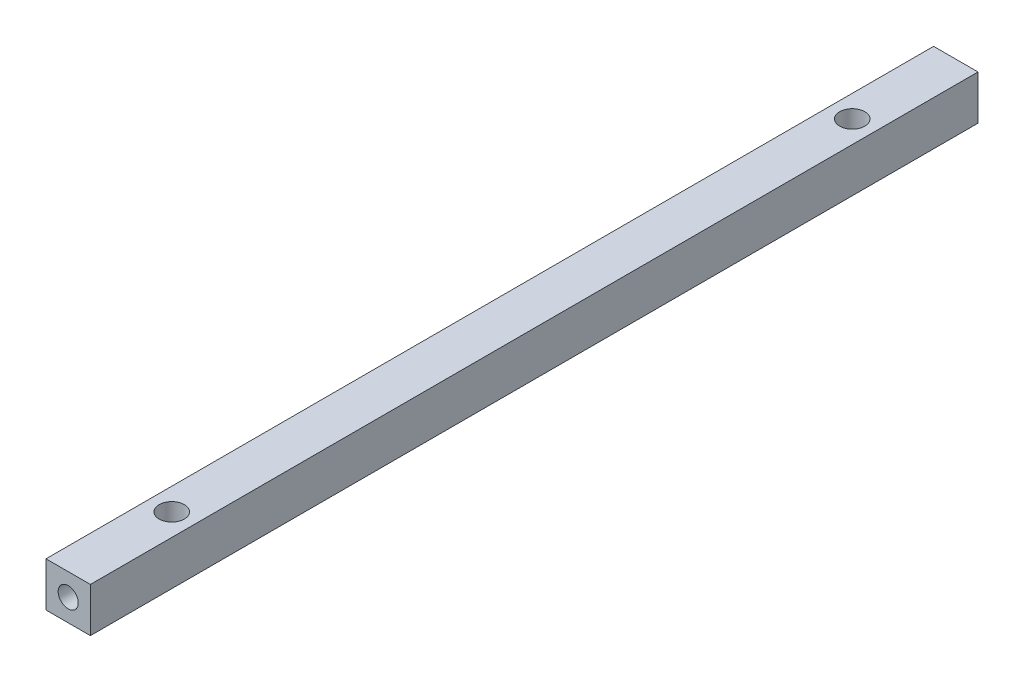
SolidWorks part; units mm, degrees
ref_plane "Ön Düzlem" through (0, 0, 0) normal (0, 0, 1) x (1, 0, 0)
ref_plane "Üst Düzlem" through (0, 0, 0) normal (0, 1, 0) x (1, 0, 0)
ref_plane "Sağ Düzlem" through (0, 0, 0) normal (1, 0, 0) x (0, 0, -1)
sketch "Çizim1" plane through (0, 0, 0) normal (0, 0, 1) x (1, 0, 0)
  line L1 (-7.5, -7.5) -> (7.5, -7.5)
  line L2 (-7.5, -7.5) -> (-7.5, 7.5)
  line L3 (-7.5, 7.5) -> (7.5, 7.5)
  line L4 (7.5, -7.5) -> (7.5, 7.5)
  line L5 (-7.5, -7.5) -> (7.5, 7.5) construction
  line L6 (-7.5, 7.5) -> (7.5, -7.5) construction
  point P0 (0, 0)
  dimension "D1" = 15
extrude "Yükseklik-Ekstrüzyon1" add sketch "Çizim1" along normal mid plane 300
hole_wizard "M8 Dişli Delik1" positions "Çizim2" profile "Çizim3" tap size "M8" standard "ISO"
sketch "Çizim2" plane through (0, 0, 150) normal (0, 0, 1) x (1, 0, 0)
  point P0 (0, 0)
sketch "Çizim3" plane through (0, 0, 150) normal (1, 0, 0) x (0, -1, 0)
  line L0 (0, 0) -> (0, 24.2929)
  line L1 (0, 24.2929) -> (3.4, 22.25)
  line L2 (3.4, 22.25) -> (3.4, 0)
  line L5 (3.4, 0) -> (0, 0)
  line L10 (0, 24.2929) -> (-3.4, 22.25) construction
  line L11 (0, -6.35) -> (0, 107.95) construction
  dimension "Tap Drill Dia." = 6.8
  dimension "Tap Drill Depth" = 22.25
  dimension "Drill Angle" = 118
cosmetic thread "Delik Dişi1" parameters "D1"=16, "D2"=8
mirror "Aynalama1" about plane through (0, 0, 0) normal (0, 0, 1) of "M8 Dişli Delik1"
cosmetic thread "Delik Dişi2" parameters "D1"=16, "D2"=8
hole_wizard "Delik1" positions "Çizim4" profile "Çizim5" legacy
sketch "Çizim4" plane through (0, -7.5, 0) normal (0, -1, 0) x (-1, 0, 0)
  line L0 (7.5, -150) -> (-7.5, -150) construction
  point P0 (0, -115)
  dimension "D1" = 35
sketch "Çizim5" plane through (0, -7.5, 115) normal (1, 0, 0) x (0, 0, -1)
  line L0 (0, 0) -> (0, 15)
  line L1 (0, 15) -> (4.25, 15)
  line L2 (4.25, 15) -> (4.25, 8)
  line L3 (4.25, 8) -> (7, 8)
  line L4 (7, 8) -> (7, 0)
  line L5 (7, 0) -> (0, 0)
  line L6 (0, 110) -> (0, -10) construction
  dimension "Diameter" = 8.5
  dimension "Depth" = 15
  dimension "C-Bore Diameter" = 14
  dimension "C-Bore Depth" = 8
mirror "Aynalama2" about plane through (0, 0, 0) normal (0, 0, 1) of "Delik1"
